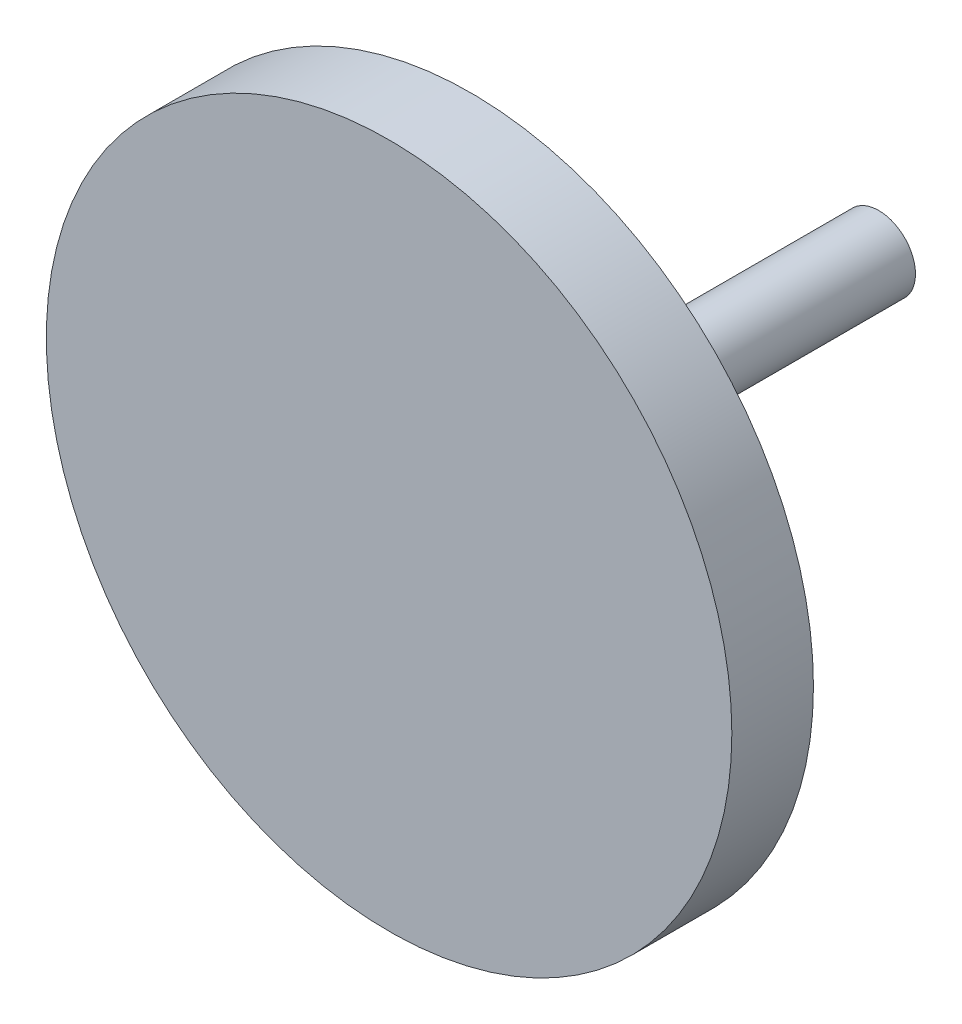
SolidWorks part; units mm, degrees
ref_plane "Front Plane" through (0, 0, 0) normal (0, 0, 1) x (1, 0, 0)
ref_plane "Top Plane" through (0, 0, 0) normal (0, 1, 0) x (1, 0, 0)
ref_plane "Right Plane" through (0, 0, 0) normal (1, 0, 0) x (0, 0, -1)
sketch "Sketch3" plane through (0, 0, 0) normal (0, 0, 1) x (1, 0, 0)
  circle A0 centre (0, 0) radius 2.25
  dimension "D1" = 4.5
extrude "Boss-Extrude1" add sketch "Sketch3" along normal mid plane 30
sketch "Sketch4" plane through (0, 0, 15) normal (0, 0, 1) x (1, 0, 0)
  circle A1 centre (0, 0) radius 21
  dimension "D1" = 42
extrude "Boss-Extrude2" add sketch "Sketch4" against normal blind 5
pattern_linear "LPattern1" [suppressed] count 2 spacing 32.5
